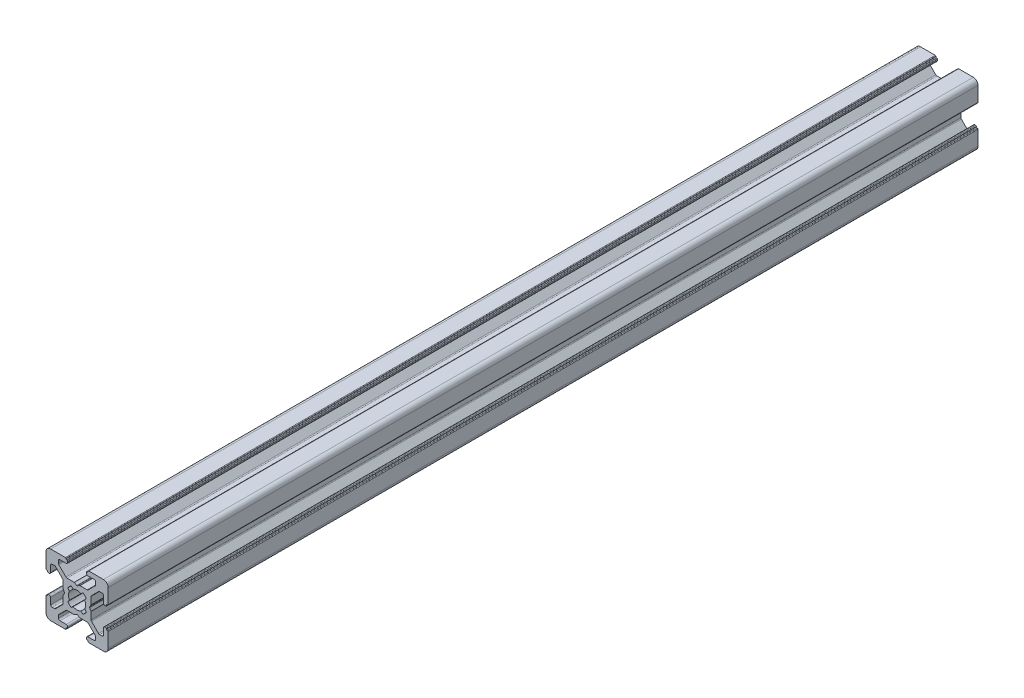
SolidWorks part; units mm, degrees
ref_plane "Front Plane" through (0, 0, 0) normal (0, 0, 1) x (1, 0, 0)
ref_plane "Top Plane" through (0, 0, 0) normal (0, 1, 0) x (1, 0, 0)
ref_plane "Right Plane" through (0, 0, 0) normal (1, 0, 0) x (0, 0, -1)
sketch "Sketch1" plane through (0, 0, 0) normal (0, 0, 1) x (1, 0, 0)
  line L0 (0, 13.3675) -> (0, -10.9159) construction
  line L1 (-12.9725, 0) -> (15.1887, 0) construction
  line L2 (-3.5, 8.5) -> (-5.5, 8.5)
  line L3 (-3.55, 9.7) -> (-3.55, 9.8)
  line L4 (-6, 7.2678) -> (-6, 8)
  line L5 (-7.2678, 6) -> (-8, 6)
  line L6 (-3.75, 10) -> (-8.5, 10)
  line L7 (-9.7, 3.55) -> (-9.8, 3.55)
  line L8 (-9.5, 3.2) -> (-9.5, 3.35)
  line L9 (-9, 3) -> (-9.3, 3)
  line L10 (-4.4732, 0.8536) -> (-4.0381, 0.1)
  line L11 (-4.5, 3.2322) -> (-4.5, 0.9536)
  line L12 (-8.5, 3.5) -> (-8.5, 5.5)
  line L13 (-10, 3.75) -> (-10, 8.5)
  line L14 (-3.5858, 4.6464) -> (-5.8536, 6.9142)
  line L15 (-4.6464, 3.5858) -> (-6.9142, 5.8536)
  line L16 (-3.2, 9.5) -> (-3.35, 9.5)
  line L17 (-3, 9) -> (-3, 9.3)
  line L18 (-0.8536, 4.4732) -> (-0.1, 4.0381)
  line L19 (-3.2322, 4.5) -> (-0.9536, 4.5)
  line L20 (-1.2582, 2.4453) -> (-1.9139, 2.9896)
  line L21 (-2.4453, 1.2582) -> (-2.9922, 1.9099)
  line L22 (3.5, -8.5) -> (5.5, -8.5)
  line L23 (3.55, -9.7) -> (3.55, -9.8)
  line L24 (6, -7.2678) -> (6, -8)
  line L25 (7.2678, -6) -> (8, -6)
  line L26 (3.75, -10) -> (8.5, -10)
  line L27 (9.7, -3.55) -> (9.8, -3.55)
  line L28 (9.5, -3.2) -> (9.5, -3.35)
  line L29 (9, -3) -> (9.3, -3)
  line L30 (4.4732, -0.8536) -> (4.0381, -0.1)
  line L31 (4.5, -3.2322) -> (4.5, -0.9536)
  line L32 (8.5, -3.5) -> (8.5, -5.5)
  line L33 (10, -3.75) -> (10, -8.5)
  line L34 (3.5858, -4.6464) -> (5.8536, -6.9142)
  line L35 (4.6464, -3.5858) -> (6.9142, -5.8536)
  line L36 (3.2, -9.5) -> (3.35, -9.5)
  line L37 (3, -9) -> (3, -9.3)
  line L38 (0.8536, -4.4732) -> (0.1, -4.0381)
  line L39 (3.2322, -4.5) -> (0.9536, -4.5)
  line L40 (1.2582, -2.4453) -> (1.9139, -2.9896)
  line L41 (2.4453, -1.2582) -> (2.9922, -1.9099)
  line L42 (-2.4453, -1.2582) -> (-2.9922, -1.9099)
  line L43 (-1.2582, -2.4453) -> (-1.9139, -2.9896)
  line L44 (-3.2322, -4.5) -> (-0.9536, -4.5)
  line L45 (-0.8536, -4.4732) -> (-0.1, -4.0381)
  line L46 (-3, -9) -> (-3, -9.3)
  line L47 (-3.2, -9.5) -> (-3.35, -9.5)
  line L48 (-4.6464, -3.5858) -> (-6.9142, -5.8536)
  line L49 (-3.5858, -4.6464) -> (-5.8536, -6.9142)
  line L50 (-10, -3.75) -> (-10, -8.5)
  line L51 (-8.5, -3.5) -> (-8.5, -5.5)
  line L52 (-4.5, -3.2322) -> (-4.5, -0.9536)
  line L53 (-4.4732, -0.8536) -> (-4.0381, -0.1)
  line L54 (-9, -3) -> (-9.3, -3)
  line L55 (-9.5, -3.2) -> (-9.5, -3.35)
  line L56 (-9.7, -3.55) -> (-9.8, -3.55)
  line L57 (2.4453, 1.2582) -> (2.9922, 1.9099)
  line L58 (1.2582, 2.4453) -> (1.9139, 2.9896)
  line L59 (3.2322, 4.5) -> (0.9536, 4.5)
  line L60 (0.8536, 4.4732) -> (0.1, 4.0381)
  line L61 (-3.75, -10) -> (-8.5, -10)
  line L62 (-7.2678, -6) -> (-8, -6)
  line L63 (-6, -7.2678) -> (-6, -8)
  line L64 (3, 9) -> (3, 9.3)
  line L65 (3.2, 9.5) -> (3.35, 9.5)
  line L66 (4.6464, 3.5858) -> (6.9142, 5.8536)
  line L67 (3.5858, 4.6464) -> (5.8536, 6.9142)
  line L68 (10, 3.75) -> (10, 8.5)
  line L69 (8.5, 3.5) -> (8.5, 5.5)
  line L70 (4.5, 3.2322) -> (4.5, 0.9536)
  line L71 (4.4732, 0.8536) -> (4.0381, 0.1)
  line L72 (9, 3) -> (9.3, 3)
  line L73 (9.5, 3.2) -> (9.5, 3.35)
  line L74 (9.7, 3.55) -> (9.8, 3.55)
  line L75 (3.75, 10) -> (8.5, 10)
  line L76 (7.2678, 6) -> (8, 6)
  line L77 (6, 7.2678) -> (6, 8)
  line L78 (3.55, 9.7) -> (3.55, 9.8)
  line L79 (3.5, 8.5) -> (5.5, 8.5)
  line L80 (-3.55, -9.7) -> (-3.55, -9.8)
  line L81 (-3.5, -8.5) -> (-5.5, -8.5)
  arc A0 (-10, 8.5) -> (-8.5, 10) centre (-8.5, 8.5) cw
  arc A1 (-8.5, 5.5) -> (-8, 6) centre (-8, 5.5) cw
  arc A2 (-7.2678, 6) -> (-6.9142, 5.8536) centre (-7.2678, 5.5) cw
  arc A3 (-5.8536, 6.9142) -> (-6, 7.2678) centre (-5.5, 7.2678) cw
  arc A4 (-6, 8) -> (-5.5, 8.5) centre (-5.5, 8) cw
  arc A5 (-9.7, 3.55) -> (-9.5, 3.35) centre (-9.7, 3.35) cw
  arc A6 (-9.8, 3.55) -> (-10, 3.75) centre (-9.8, 3.75) cw
  arc A7 (-9.3, 3) -> (-9.5, 3.2) centre (-9.3, 3.2) cw
  arc A8 (-8.5, 3.5) -> (-9, 3) centre (-9, 3.5) cw
  arc A9 (-4.6464, 3.5858) -> (-4.5, 3.2322) centre (-5, 3.2322) cw
  arc A10 (-4.4732, 0.8536) -> (-4.5, 0.9536) centre (-4.3, 0.9536) cw
  arc A11 (-4.0381, 0.1) -> (-4.0381, -0.1) centre (-4.2113, 0) cw
  arc A12 (-3.2, 9.5) -> (-3, 9.3) centre (-3.2, 9.3) cw
  arc A13 (-0.9536, 4.5) -> (-0.8536, 4.4732) centre (-0.9536, 4.3) cw
  arc A14 (-2.9922, 1.9099) -> (-1.9139, 2.9896) centre (0, 0) cw
  arc A15 (-3.2322, 4.5) -> (-3.5858, 4.6464) centre (-3.2322, 5) cw
  arc A16 (-3.75, 10) -> (-3.55, 9.8) centre (-3.75, 9.8) cw
  arc A17 (-3.35, 9.5) -> (-3.55, 9.7) centre (-3.35, 9.7) cw
  arc A18 (2.4453, -1.2582) -> (2.4453, 1.2582) centre (0, 0) ccw
  arc A19 (-3, 9) -> (-3.5, 8.5) centre (-3.5, 9) cw
  arc A20 (-2.4453, -1.2582) -> (-2.4453, 1.2582) centre (0, 0) cw
  arc A21 (10, -8.5) -> (8.5, -10) centre (8.5, -8.5) cw
  arc A22 (8.5, -5.5) -> (8, -6) centre (8, -5.5) cw
  arc A23 (7.2678, -6) -> (6.9142, -5.8536) centre (7.2678, -5.5) cw
  arc A24 (5.8536, -6.9142) -> (6, -7.2678) centre (5.5, -7.2678) cw
  arc A25 (6, -8) -> (5.5, -8.5) centre (5.5, -8) cw
  arc A26 (9.7, -3.55) -> (9.5, -3.35) centre (9.7, -3.35) cw
  arc A27 (9.8, -3.55) -> (10, -3.75) centre (9.8, -3.75) cw
  arc A28 (9.3, -3) -> (9.5, -3.2) centre (9.3, -3.2) cw
  arc A29 (8.5, -3.5) -> (9, -3) centre (9, -3.5) cw
  arc A30 (4.6464, -3.5858) -> (4.5, -3.2322) centre (5, -3.2322) cw
  arc A31 (4.4732, -0.8536) -> (4.5, -0.9536) centre (4.3, -0.9536) cw
  arc A32 (3.2, -9.5) -> (3, -9.3) centre (3.2, -9.3) cw
  arc A33 (-0.1, -4.0381) -> (0.1, -4.0381) centre (0, -4.2113) cw
  arc A34 (0.9536, -4.5) -> (0.8536, -4.4732) centre (0.9536, -4.3) cw
  arc A35 (2.9922, -1.9099) -> (1.9139, -2.9896) centre (0, 0) cw
  arc A36 (1.2582, -2.4453) -> (-1.2582, -2.4453) centre (0, 0) cw
  arc A37 (3.2322, -4.5) -> (3.5858, -4.6464) centre (3.2322, -5) cw
  arc A38 (3.75, -10) -> (3.55, -9.8) centre (3.75, -9.8) cw
  arc A39 (3.35, -9.5) -> (3.55, -9.7) centre (3.35, -9.7) cw
  arc A40 (3, -9) -> (3.5, -8.5) centre (3.5, -9) cw
  arc A41 (-3, -9) -> (-3.5, -8.5) centre (-3.5, -9) ccw
  arc A42 (-3.35, -9.5) -> (-3.55, -9.7) centre (-3.35, -9.7) ccw
  arc A43 (-3.75, -10) -> (-3.55, -9.8) centre (-3.75, -9.8) ccw
  arc A44 (-3.2322, -4.5) -> (-3.5858, -4.6464) centre (-3.2322, -5) ccw
  arc A45 (-2.9922, -1.9099) -> (-1.9139, -2.9896) centre (0, 0) ccw
  arc A46 (-0.9536, -4.5) -> (-0.8536, -4.4732) centre (-0.9536, -4.3) ccw
  arc A47 (-3.2, -9.5) -> (-3, -9.3) centre (-3.2, -9.3) ccw
  arc A48 (-4.4732, -0.8536) -> (-4.5, -0.9536) centre (-4.3, -0.9536) ccw
  arc A49 (3, 9) -> (3.5, 8.5) centre (3.5, 9) ccw
  arc A50 (3.35, 9.5) -> (3.55, 9.7) centre (3.35, 9.7) ccw
  arc A51 (3.75, 10) -> (3.55, 9.8) centre (3.75, 9.8) ccw
  arc A52 (3.2322, 4.5) -> (3.5858, 4.6464) centre (3.2322, 5) ccw
  arc A53 (1.2582, 2.4453) -> (-1.2582, 2.4453) centre (0, 0) ccw
  arc A54 (-4.6464, -3.5858) -> (-4.5, -3.2322) centre (-5, -3.2322) ccw
  arc A55 (-8.5, -3.5) -> (-9, -3) centre (-9, -3.5) ccw
  arc A56 (-9.3, -3) -> (-9.5, -3.2) centre (-9.3, -3.2) ccw
  arc A57 (-9.8, -3.55) -> (-10, -3.75) centre (-9.8, -3.75) ccw
  arc A58 (-9.7, -3.55) -> (-9.5, -3.35) centre (-9.7, -3.35) ccw
  arc A59 (-6, -8) -> (-5.5, -8.5) centre (-5.5, -8) ccw
  arc A60 (2.9922, 1.9099) -> (1.9139, 2.9896) centre (0, 0) ccw
  arc A61 (0.9536, 4.5) -> (0.8536, 4.4732) centre (0.9536, 4.3) ccw
  arc A62 (-0.1, 4.0381) -> (0.1, 4.0381) centre (0, 4.2113) ccw
  arc A63 (-5.8536, -6.9142) -> (-6, -7.2678) centre (-5.5, -7.2678) ccw
  arc A64 (-7.2678, -6) -> (-6.9142, -5.8536) centre (-7.2678, -5.5) ccw
  arc A65 (-8.5, -5.5) -> (-8, -6) centre (-8, -5.5) ccw
  arc A66 (-10, -8.5) -> (-8.5, -10) centre (-8.5, -8.5) ccw
  arc A67 (3.2, 9.5) -> (3, 9.3) centre (3.2, 9.3) ccw
  arc A68 (4.0381, 0.1) -> (4.0381, -0.1) centre (4.2113, 0) ccw
  arc A69 (4.4732, 0.8536) -> (4.5, 0.9536) centre (4.3, 0.9536) ccw
  arc A70 (4.6464, 3.5858) -> (4.5, 3.2322) centre (5, 3.2322) ccw
  arc A71 (8.5, 3.5) -> (9, 3) centre (9, 3.5) ccw
  arc A72 (9.3, 3) -> (9.5, 3.2) centre (9.3, 3.2) ccw
  arc A73 (9.8, 3.55) -> (10, 3.75) centre (9.8, 3.75) ccw
  arc A74 (9.7, 3.55) -> (9.5, 3.35) centre (9.7, 3.35) ccw
  arc A75 (6, 8) -> (5.5, 8.5) centre (5.5, 8) ccw
  arc A76 (5.8536, 6.9142) -> (6, 7.2678) centre (5.5, 7.2678) ccw
  arc A77 (7.2678, 6) -> (6.9142, 5.8536) centre (7.2678, 5.5) ccw
  arc A78 (8.5, 5.5) -> (8, 6) centre (8, 5.5) ccw
  arc A79 (10, 8.5) -> (8.5, 10) centre (8.5, 8.5) ccw
  dimension "D4" = 5.5
  dimension "D1" = 6
  dimension "D2" = 20
  dimension "D3" = 20
  dimension "D5" = 5.5
  dimension "D6" = 10
  dimension "D7" = 6
  dimension "D8" = 6
  dimension "D9" = 6
extrude "Extrude1" add sketch "Sketch1" along normal blind 280
